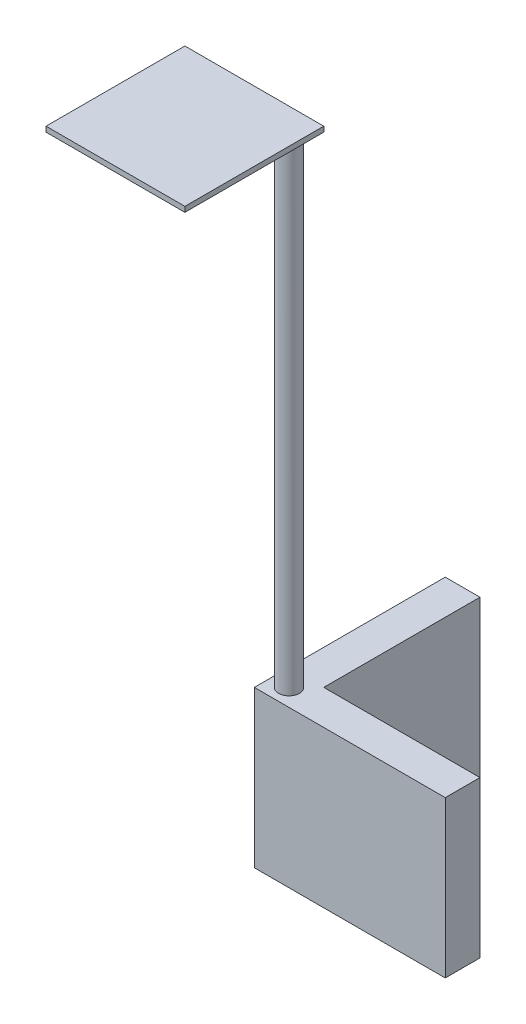
SolidWorks part; units mm, degrees
ref_plane "Plan de face" through (0, 0, 0) normal (0, 0, 1) x (1, 0, 0)
ref_plane "Plan de dessus" through (0, 0, 0) normal (0, 1, 0) x (1, 0, 0)
ref_plane "Plan de droite" through (0, 0, 0) normal (1, 0, 0) x (0, 0, -1)
sketch "Esquisse1" plane through (0, 0, 0) normal (1, 0, 0) x (0, 0, -1)
  line L1 (75.9293, 32.036) -> (-14.0707, 32.036)
  line L2 (75.9293, 32.036) -> (75.9293, -57.964)
  line L3 (75.9293, -57.964) -> (-14.0707, -57.964)
  line L4 (-14.0707, 32.036) -> (-14.0707, -57.964)
  dimension "D1" = 90
  dimension "D2" = 90
extrude "Boss.-Extru.1" add sketch "Esquisse1" along normal blind 20
sketch "Esquisse5" plane through (0, 0, 14.0707) normal (0, 0, 1) x (1, 0, 0)
  line L0 (20, 32.036) -> (20, -57.964) construction
  line L1 (0, 32.036) -> (110, 32.036)
  line L2 (0, 32.036) -> (0, -57.964)
  line L3 (0, -57.964) -> (110, -57.964)
  line L4 (110, 32.036) -> (110, -57.964)
  dimension "D1" = 90
  dimension "D2" = 110
  dimension "D3" = 90
extrude "Boss.-Extru.5" add sketch "Esquisse5" along normal blind 20
sketch "Esquisse2" plane through (0, 32.036, 0) normal (0, 1, 0) x (1, 0, 0)
  line L0 (20, 75.9293) -> (20, -14.0707) construction
  line L2 (110, -34.0707) -> (0, -34.0707) construction
  circle A0 centre (10, -24.0707) radius 6
  dimension "D1" = 10
  dimension "D2" = 10
extrude "Boss.-Extru.2" add sketch "Esquisse2" along normal blind 277
sketch "Esquisse3" plane through (0, 309.036, 0) normal (0, 1, 0) x (1, 0, 0)
  line L1 (-60, -94.0707) -> (20, -94.0707)
  line L2 (-60, -94.0707) -> (-60, -14.0707)
  line L3 (-60, -14.0707) -> (20, -14.0707)
  line L4 (20, -94.0707) -> (20, -14.0707)
  circle A0 centre (10, -24.0707) radius 6 construction
  dimension "D4" = 10
  dimension "D1" = 80
  dimension "D2" = 80
  dimension "D3" = 70
extrude "Boss.-Extru.3" add sketch "Esquisse3" along normal blind 2.9
sketch "Esquisse4" plane through (0, 311.936, 0) normal (0, 1, 0) x (1, 0, 0)
  line L1 (-60, -14.0707) -> (20, -14.0707)
  line L2 (-60, -14.0707) -> (-60, -94.0707)
  line L3 (-60, -94.0707) -> (20, -94.0707)
  line L4 (20, -14.0707) -> (20, -94.0707)
extrude "Boss.-Extru.4" add sketch "Esquisse4" along normal blind 0.1
